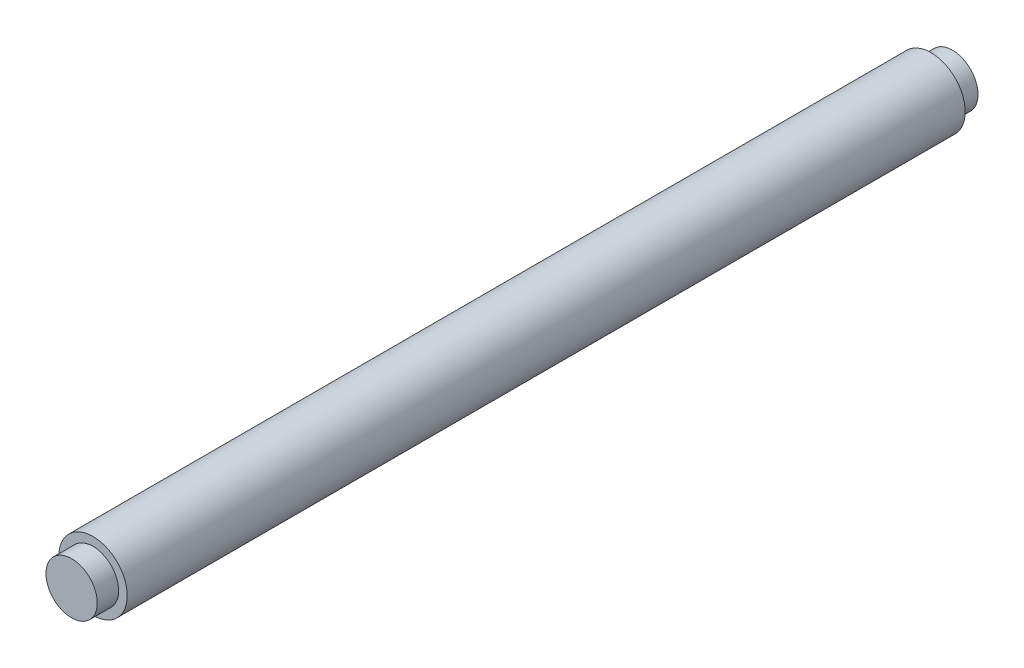
SolidWorks part; units mm, degrees
ref_plane "Plan1" through (0, 0, 0) normal (0, 0, 1) x (1, 0, 0)
ref_plane "Plan2" through (0, 0, 0) normal (0, 1, 0) x (1, 0, 0)
ref_plane "Plan3" through (0, 0, 0) normal (1, 0, 0) x (0, 0, -1)
sketch "Esquisse1" plane through (0, 0, 0) normal (0, 0, 1) x (1, 0, 0)
  circle A0 centre (0, 0) radius 4
  dimension "D1" = 8
extrude "Base-Extrusion" add sketch "Esquisse1" along normal blind 98
sketch "Esquisse2" plane through (0, 0, 98) normal (0, 0, 1) x (1, 0, 0)
  circle A0 centre (0, 0) radius 3
  dimension "D1" = 6
extrude "Boss.-Extru.1" add sketch "Esquisse2" along normal blind 2.5
sketch "Esquisse3" plane through (0, 0, 0) normal (0, 0, -1) x (-1, 0, 0)
  circle A0 centre (0, 0) radius 3
  dimension "D1" = 6
extrude "Boss.-Extru.2" add sketch "Esquisse3" along normal blind 2.5
